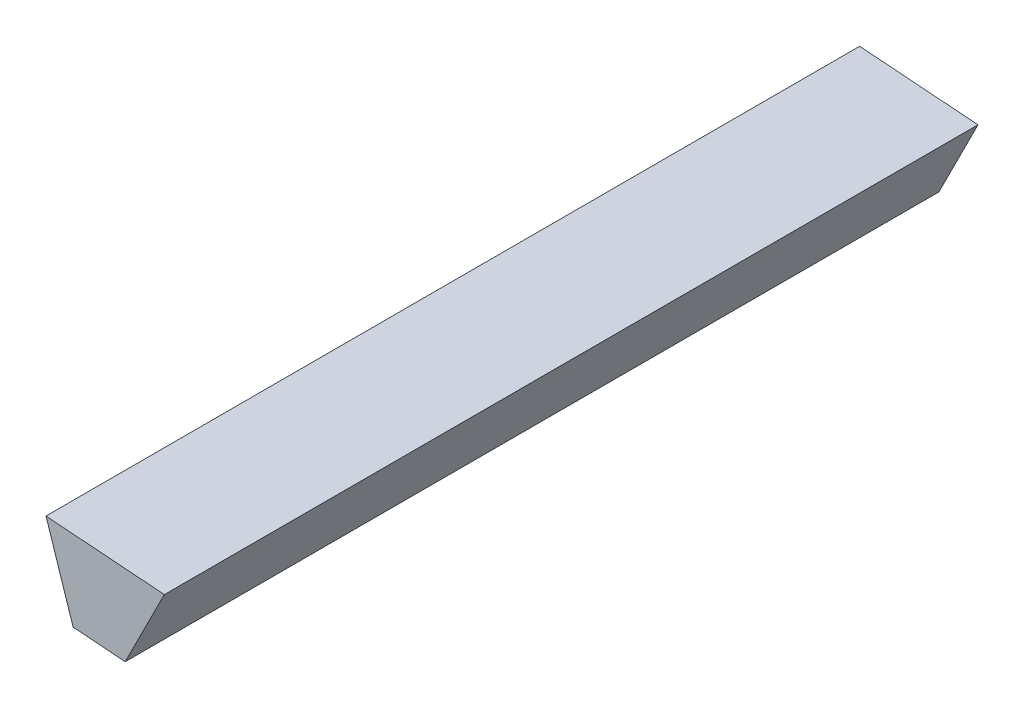
SolidWorks part; units mm, degrees
ref_plane "Спереди" through (0, 0, 0) normal (0, 0, 1) x (1, 0, 0)
ref_plane "Сверху" through (0, 0, 0) normal (0, 1, 0) x (1, 0, 0)
ref_plane "Справа" through (0, 0, 0) normal (1, 0, 0) x (0, 0, -1)
sketch "Эскиз1" plane through (0, 0, 0) normal (0, 0, 1) x (1, 0, 0)
  line L0 (0, 0) -> (0, 56) construction
  line L1 (-2, 55.9643) -> (-3, 52.915)
  line L2 (2, 55.9643) -> (3, 52.915)
  line L3 (6.3634, 55.6373) -> (4.9201, 52.7711)
  line L4 (10.3187, 55.0411) -> (10.8531, 51.8769)
  line L5 (14.5846, 54.0674) -> (12.7303, 51.4484)
  line L6 (18.4069, 52.8884) -> (18.4637, 49.6799)
  line L7 (22.4801, 51.2898) -> (20.2561, 48.9764)
  line L8 (26.0839, 49.5543) -> (25.6619, 46.3731)
  line L9 (29.8733, 47.3665) -> (27.3294, 45.4104)
  line L10 (33.1783, 45.1132) -> (32.2868, 42.0305)
  line L11 (36.5993, 42.3851) -> (33.7922, 40.83)
  line L12 (39.5315, 39.6644) -> (38.1905, 36.7489)
  line L13 (42.5077, 36.4568) -> (39.5002, 35.3375)
  line L14 (45.0016, 33.3295) -> (43.2411, 30.6465)
  line L15 (47.4665, 29.7142) -> (44.3258, 29.0556)
  line L16 (49.4665, 26.2501) -> (47.3258, 23.8594)
  line L17 (51.365, 22.3078) -> (48.1612, 22.1247)
  line L18 (52.8264, 18.5843) -> (50.3532, 16.5394)
  line L19 (54.1161, 14.4031) -> (50.9208, 14.6995)
  line L20 (55.0062, 10.5034) -> (52.2559, 8.8499)
  line L21 (55.6583, 6.1766) -> (52.5429, 6.946)
  line L22 (55.9572, 2.1878) -> (52.9913, 0.9627)
  line L23 (55.9572, -2.1878) -> (52.9913, -0.9627)
  line L24 (55.6583, -6.1766) -> (52.5429, -6.946)
  line L25 (55.0062, -10.5034) -> (52.2559, -8.8499)
  line L26 (54.1161, -14.4031) -> (50.9208, -14.6995)
  line L27 (52.8264, -18.5843) -> (50.3532, -16.5394)
  line L28 (51.365, -22.3078) -> (48.1612, -22.1247)
  line L29 (49.4665, -26.2501) -> (47.3258, -23.8594)
  line L30 (47.4665, -29.7142) -> (44.3258, -29.0556)
  line L31 (45.0016, -33.3295) -> (43.2411, -30.6465)
  line L32 (42.5077, -36.4568) -> (39.5002, -35.3375)
  line L33 (39.5315, -39.6644) -> (38.1905, -36.7489)
  line L34 (36.5993, -42.3851) -> (33.7922, -40.83)
  line L35 (33.1783, -45.1132) -> (32.2868, -42.0305)
  line L36 (29.8733, -47.3665) -> (27.3294, -45.4104)
  line L37 (26.0839, -49.5543) -> (25.6619, -46.3731)
  line L38 (22.4801, -51.2898) -> (20.2561, -48.9764)
  line L39 (18.4069, -52.8884) -> (18.4637, -49.6799)
  line L40 (14.5846, -54.0674) -> (12.7303, -51.4484)
  line L41 (10.3187, -55.0411) -> (10.8531, -51.8769)
  line L42 (6.3634, -55.6373) -> (4.9201, -52.7711)
  line L43 (2, -55.9643) -> (3, -52.915)
  line L44 (-2, -55.9643) -> (-3, -52.915)
  line L45 (-6.3634, -55.6373) -> (-4.9201, -52.7711)
  line L46 (-10.3187, -55.0411) -> (-10.8531, -51.8769)
  line L47 (-14.5846, -54.0674) -> (-12.7303, -51.4484)
  line L48 (-18.4069, -52.8884) -> (-18.4637, -49.6799)
  line L49 (-22.4801, -51.2898) -> (-20.2561, -48.9764)
  line L50 (-26.0839, -49.5543) -> (-25.6619, -46.3731)
  line L51 (-29.8733, -47.3665) -> (-27.3294, -45.4104)
  line L52 (-33.1783, -45.1132) -> (-32.2868, -42.0305)
  line L53 (-36.5993, -42.3851) -> (-33.7922, -40.83)
  line L54 (-39.5315, -39.6644) -> (-38.1905, -36.7489)
  line L55 (-42.5077, -36.4568) -> (-39.5002, -35.3375)
  line L56 (-45.0016, -33.3295) -> (-43.2411, -30.6465)
  line L57 (-47.4665, -29.7142) -> (-44.3258, -29.0556)
  line L58 (-49.4665, -26.2501) -> (-47.3258, -23.8594)
  line L59 (-51.365, -22.3078) -> (-48.1612, -22.1247)
  line L60 (-52.8264, -18.5843) -> (-50.3532, -16.5394)
  line L61 (-54.1161, -14.4031) -> (-50.9208, -14.6995)
  line L62 (-55.0062, -10.5034) -> (-52.2559, -8.8499)
  line L63 (-55.6583, -6.1766) -> (-52.5429, -6.946)
  line L64 (-55.9572, -2.1878) -> (-52.9913, -0.9627)
  line L65 (-55.9572, 2.1878) -> (-52.9913, 0.9627)
  line L66 (-55.6583, 6.1766) -> (-52.5429, 6.946)
  line L67 (-55.0062, 10.5034) -> (-52.2559, 8.8499)
  line L68 (-54.1161, 14.4031) -> (-50.9208, 14.6995)
  line L69 (-52.8264, 18.5843) -> (-50.3532, 16.5394)
  line L70 (-51.365, 22.3078) -> (-48.1612, 22.1247)
  line L71 (-49.4665, 26.2501) -> (-47.3258, 23.8594)
  line L72 (-47.4665, 29.7142) -> (-44.3258, 29.0556)
  line L73 (-45.0016, 33.3295) -> (-43.2411, 30.6465)
  line L74 (-42.5077, 36.4568) -> (-39.5002, 35.3375)
  line L75 (-39.5315, 39.6644) -> (-38.1905, 36.7489)
  line L76 (-36.5993, 42.3851) -> (-33.7922, 40.83)
  line L77 (-33.1783, 45.1132) -> (-32.2868, 42.0305)
  line L78 (-29.8733, 47.3665) -> (-27.3294, 45.4104)
  line L79 (-26.0839, 49.5543) -> (-25.6619, 46.3731)
  line L80 (-22.4801, 51.2898) -> (-20.2561, 48.9764)
  line L81 (-18.4069, 52.8884) -> (-18.4637, 49.6799)
  line L82 (-14.5846, 54.0674) -> (-12.7303, 51.4484)
  line L83 (-10.3187, 55.0411) -> (-10.8531, 51.8769)
  line L84 (-6.3634, 55.6373) -> (-4.9201, 52.7711)
  arc A0 (2, 55.9643) -> (-2, 55.9643) centre (0, 0) ccw
  arc A1 (-3, 52.915) -> (-3.965, 52.8515) centre (0, 0) ccw
  arc A2 (3, 52.915) -> (3.965, 52.8515) centre (0, 0) cw
  arc A3 (4.9201, 52.7711) -> (3.9564, 52.8521) centre (0, 0) ccw
  arc A4 (10.3187, 55.0411) -> (6.3634, 55.6373) centre (0, 0) ccw
  arc A5 (10.8531, 51.8769) -> (11.7978, 51.6702) centre (0, 0) cw
  arc A6 (12.7303, 51.4484) -> (11.7894, 51.6721) centre (0, 0) ccw
  arc A7 (18.4069, 52.8884) -> (14.5846, 54.0674) centre (0, 0) ccw
  arc A8 (18.4637, 49.6799) -> (19.3671, 49.3347) centre (0, 0) cw
  arc A9 (20.2561, 48.9764) -> (19.3591, 49.3379) centre (0, 0) ccw
  arc A10 (26.0839, 49.5543) -> (22.4801, 51.2898) centre (0, 0) ccw
  arc A11 (25.6619, 46.3731) -> (26.5037, 45.8972) centre (0, 0) cw
  arc A12 (27.3294, 45.4104) -> (26.4963, 45.9015) centre (0, 0) ccw
  arc A13 (33.1783, 45.1132) -> (29.8733, 47.3665) centre (0, 0) ccw
  arc A14 (32.2868, 42.0305) -> (33.0483, 41.4344) centre (0, 0) cw
  arc A15 (33.7922, 40.83) -> (33.0416, 41.4398) centre (0, 0) ccw
  arc A16 (39.5315, 39.6644) -> (36.5993, 42.3851) centre (0, 0) ccw
  arc A17 (38.1905, 36.7489) -> (38.8547, 36.046) centre (0, 0) cw
  arc A18 (39.5002, 35.3375) -> (38.8488, 36.0523) centre (0, 0) ccw
  arc A19 (45.0016, 33.3295) -> (42.5077, 36.4568) centre (0, 0) ccw
  arc A20 (43.2411, 30.6465) -> (43.7931, 29.8524) centre (0, 0) cw
  arc A21 (44.3258, 29.0556) -> (43.7882, 29.8595) centre (0, 0) ccw
  arc A22 (49.4665, 26.2501) -> (47.4665, 29.7142) centre (0, 0) ccw
  arc A23 (47.3258, 23.8594) -> (47.7532, 22.9919) centre (0, 0) cw
  arc A24 (48.1612, 22.1247) -> (47.7495, 22.9997) centre (0, 0) ccw
  arc A25 (52.8264, 18.5843) -> (51.365, 22.3078) centre (0, 0) ccw
  arc A26 (50.3532, 16.5394) -> (50.6466, 15.6179) centre (0, 0) cw
  arc A27 (50.9208, 14.6995) -> (50.6441, 15.6261) centre (0, 0) ccw
  arc A28 (55.0062, 10.5034) -> (54.1161, 14.4031) centre (0, 0) ccw
  arc A29 (52.2559, 8.8499) -> (52.4087, 7.895) centre (0, 0) cw
  arc A30 (52.5429, 6.946) -> (52.4074, 7.9035) centre (0, 0) ccw
  arc A31 (55.9572, 2.1878) -> (55.6583, 6.1766) centre (0, 0) ccw
  arc A32 (52.9913, 0.9627) -> (53, -0.0043) centre (0, 0) cw
  arc A33 (52.9913, -0.9627) -> (53, 0.0043) centre (0, 0) ccw
  arc A34 (55.6583, -6.1766) -> (55.9572, -2.1878) centre (0, 0) ccw
  arc A35 (52.5429, -6.946) -> (52.4074, -7.9035) centre (0, 0) cw
  arc A36 (52.2559, -8.8499) -> (52.4087, -7.895) centre (0, 0) ccw
  arc A37 (54.1161, -14.4031) -> (55.0062, -10.5034) centre (0, 0) ccw
  arc A38 (50.9208, -14.6995) -> (50.6441, -15.6261) centre (0, 0) cw
  arc A39 (50.3532, -16.5394) -> (50.6466, -15.6179) centre (0, 0) ccw
  arc A40 (51.365, -22.3078) -> (52.8264, -18.5843) centre (0, 0) ccw
  arc A41 (48.1612, -22.1247) -> (47.7495, -22.9997) centre (0, 0) cw
  arc A42 (47.3258, -23.8594) -> (47.7532, -22.9919) centre (0, 0) ccw
  arc A43 (47.4665, -29.7142) -> (49.4665, -26.2501) centre (0, 0) ccw
  arc A44 (44.3258, -29.0556) -> (43.7882, -29.8595) centre (0, 0) cw
  arc A45 (43.2411, -30.6465) -> (43.7931, -29.8524) centre (0, 0) ccw
  arc A46 (42.5077, -36.4568) -> (45.0016, -33.3295) centre (0, 0) ccw
  arc A47 (39.5002, -35.3375) -> (38.8488, -36.0523) centre (0, 0) cw
  arc A48 (38.1905, -36.7489) -> (38.8547, -36.046) centre (0, 0) ccw
  arc A49 (36.5993, -42.3851) -> (39.5315, -39.6644) centre (0, 0) ccw
  arc A50 (33.7922, -40.83) -> (33.0416, -41.4398) centre (0, 0) cw
  arc A51 (32.2868, -42.0305) -> (33.0483, -41.4344) centre (0, 0) ccw
  arc A52 (29.8733, -47.3665) -> (33.1783, -45.1132) centre (0, 0) ccw
  arc A53 (27.3294, -45.4104) -> (26.4963, -45.9015) centre (0, 0) cw
  arc A54 (25.6619, -46.3731) -> (26.5037, -45.8972) centre (0, 0) ccw
  arc A55 (22.4801, -51.2898) -> (26.0839, -49.5543) centre (0, 0) ccw
  arc A56 (20.2561, -48.9764) -> (19.3591, -49.3379) centre (0, 0) cw
  arc A57 (18.4637, -49.6799) -> (19.3671, -49.3347) centre (0, 0) ccw
  arc A58 (14.5846, -54.0674) -> (18.4069, -52.8884) centre (0, 0) ccw
  arc A59 (12.7303, -51.4484) -> (11.7894, -51.6721) centre (0, 0) cw
  arc A60 (10.8531, -51.8769) -> (11.7978, -51.6702) centre (0, 0) ccw
  arc A61 (6.3634, -55.6373) -> (10.3187, -55.0411) centre (0, 0) ccw
  arc A62 (4.9201, -52.7711) -> (3.9564, -52.8521) centre (0, 0) cw
  arc A63 (3, -52.915) -> (3.965, -52.8515) centre (0, 0) ccw
  arc A64 (-2, -55.9643) -> (2, -55.9643) centre (0, 0) ccw
  arc A65 (-3, -52.915) -> (-3.965, -52.8515) centre (0, 0) cw
  arc A66 (-4.9201, -52.7711) -> (-3.9564, -52.8521) centre (0, 0) ccw
  arc A67 (-10.3187, -55.0411) -> (-6.3634, -55.6373) centre (0, 0) ccw
  arc A68 (-10.8531, -51.8769) -> (-11.7978, -51.6702) centre (0, 0) cw
  arc A69 (-12.7303, -51.4484) -> (-11.7894, -51.6721) centre (0, 0) ccw
  arc A70 (-18.4069, -52.8884) -> (-14.5846, -54.0674) centre (0, 0) ccw
  arc A71 (-18.4637, -49.6799) -> (-19.3671, -49.3347) centre (0, 0) cw
  arc A72 (-20.2561, -48.9764) -> (-19.3591, -49.3379) centre (0, 0) ccw
  arc A73 (-26.0839, -49.5543) -> (-22.4801, -51.2898) centre (0, 0) ccw
  arc A74 (-25.6619, -46.3731) -> (-26.5037, -45.8972) centre (0, 0) cw
  arc A75 (-27.3294, -45.4104) -> (-26.4963, -45.9015) centre (0, 0) ccw
  arc A76 (-33.1783, -45.1132) -> (-29.8733, -47.3665) centre (0, 0) ccw
  arc A77 (-32.2868, -42.0305) -> (-33.0483, -41.4344) centre (0, 0) cw
  arc A78 (-33.7922, -40.83) -> (-33.0416, -41.4398) centre (0, 0) ccw
  arc A79 (-39.5315, -39.6644) -> (-36.5993, -42.3851) centre (0, 0) ccw
  arc A80 (-38.1905, -36.7489) -> (-38.8547, -36.046) centre (0, 0) cw
  arc A81 (-39.5002, -35.3375) -> (-38.8488, -36.0523) centre (0, 0) ccw
  arc A82 (-45.0016, -33.3295) -> (-42.5077, -36.4568) centre (0, 0) ccw
  arc A83 (-43.2411, -30.6465) -> (-43.7931, -29.8524) centre (0, 0) cw
  arc A84 (-44.3258, -29.0556) -> (-43.7882, -29.8595) centre (0, 0) ccw
  arc A85 (-49.4665, -26.2501) -> (-47.4665, -29.7142) centre (0, 0) ccw
  arc A86 (-47.3258, -23.8594) -> (-47.7532, -22.9919) centre (0, 0) cw
  arc A87 (-48.1612, -22.1247) -> (-47.7495, -22.9997) centre (0, 0) ccw
  arc A88 (-52.8264, -18.5843) -> (-51.365, -22.3078) centre (0, 0) ccw
  arc A89 (-50.3532, -16.5394) -> (-50.6466, -15.6179) centre (0, 0) cw
  arc A90 (-50.9208, -14.6995) -> (-50.6441, -15.6261) centre (0, 0) ccw
  arc A91 (-55.0062, -10.5034) -> (-54.1161, -14.4031) centre (0, 0) ccw
  arc A92 (-52.2559, -8.8499) -> (-52.4087, -7.895) centre (0, 0) cw
  arc A93 (-52.5429, -6.946) -> (-52.4074, -7.9035) centre (0, 0) ccw
  arc A94 (-55.9572, -2.1878) -> (-55.6583, -6.1766) centre (0, 0) ccw
  arc A95 (-52.9913, -0.9627) -> (-53, 0.0043) centre (0, 0) cw
  arc A96 (-52.9913, 0.9627) -> (-53, -0.0043) centre (0, 0) ccw
  arc A97 (-55.6583, 6.1766) -> (-55.9572, 2.1878) centre (0, 0) ccw
  arc A98 (-52.5429, 6.946) -> (-52.4074, 7.9035) centre (0, 0) cw
  arc A99 (-52.2559, 8.8499) -> (-52.4087, 7.895) centre (0, 0) ccw
  arc A100 (-54.1161, 14.4031) -> (-55.0062, 10.5034) centre (0, 0) ccw
  arc A101 (-50.9208, 14.6995) -> (-50.6441, 15.6261) centre (0, 0) cw
  arc A102 (-50.3532, 16.5394) -> (-50.6466, 15.6179) centre (0, 0) ccw
  arc A103 (-51.365, 22.3078) -> (-52.8264, 18.5843) centre (0, 0) ccw
  arc A104 (-48.1612, 22.1247) -> (-47.7495, 22.9997) centre (0, 0) cw
  arc A105 (-47.3258, 23.8594) -> (-47.7532, 22.9919) centre (0, 0) ccw
  arc A106 (-47.4665, 29.7142) -> (-49.4665, 26.2501) centre (0, 0) ccw
  arc A107 (-44.3258, 29.0556) -> (-43.7882, 29.8595) centre (0, 0) cw
  arc A108 (-43.2411, 30.6465) -> (-43.7931, 29.8524) centre (0, 0) ccw
  arc A109 (-42.5077, 36.4568) -> (-45.0016, 33.3295) centre (0, 0) ccw
  arc A110 (-39.5002, 35.3375) -> (-38.8488, 36.0523) centre (0, 0) cw
  arc A111 (-38.1905, 36.7489) -> (-38.8547, 36.046) centre (0, 0) ccw
  arc A112 (-36.5993, 42.3851) -> (-39.5315, 39.6644) centre (0, 0) ccw
  arc A113 (-33.7922, 40.83) -> (-33.0416, 41.4398) centre (0, 0) cw
  arc A114 (-32.2868, 42.0305) -> (-33.0483, 41.4344) centre (0, 0) ccw
  arc A115 (-29.8733, 47.3665) -> (-33.1783, 45.1132) centre (0, 0) ccw
  arc A116 (-27.3294, 45.4104) -> (-26.4963, 45.9015) centre (0, 0) cw
  arc A117 (-25.6619, 46.3731) -> (-26.5037, 45.8972) centre (0, 0) ccw
  arc A118 (-22.4801, 51.2898) -> (-26.0839, 49.5543) centre (0, 0) ccw
  arc A119 (-20.2561, 48.9764) -> (-19.3591, 49.3379) centre (0, 0) cw
  arc A120 (-18.4637, 49.6799) -> (-19.3671, 49.3347) centre (0, 0) ccw
  arc A121 (-14.5846, 54.0674) -> (-18.4069, 52.8884) centre (0, 0) ccw
  arc A122 (-12.7303, 51.4484) -> (-11.7894, 51.6721) centre (0, 0) cw
  arc A123 (-10.8531, 51.8769) -> (-11.7978, 51.6702) centre (0, 0) ccw
  arc A124 (-6.3634, 55.6373) -> (-10.3187, 55.0411) centre (0, 0) ccw
  arc A125 (-4.9201, 52.7711) -> (-3.9564, 52.8521) centre (0, 0) cw
  circle A126 centre (0, 0) radius 50
  point P258 (0, 0)
  dimension "D1" = 56
  dimension "D3" = 53
  dimension "D7" = 100
  dimension "D2" = 2
  dimension "D4" = 3
  dimension "D5" = 3.965
  dimension "D6" = 42
extrude "Бобышка-Вытянуть1" add sketch "Эскиз1" along normal mid plane 30
sketch "Эскиз2" plane through (0, 0, -15) normal (0, 0, -1) x (-1, 0, 0)
  line L0 (0, 0) -> (0, 41.684) construction
  line L1 (3.4537, 43) -> (-3.4537, 43)
  line L2 (-8.2776, 36.6844) -> (-4.8039, 23.9475)
  line L3 (-0.9448, 21) -> (0.9448, 21)
  line L4 (8.2776, 36.6844) -> (4.8039, 23.9475)
  line L5 (41.9627, 10.003) -> (39.8282, 16.5724)
  line L6 (32.331, 19.2085) -> (21.291, 11.9689)
  line L7 (37.4469, 3.4637) -> (24.2599, 2.8314)
  line L8 (19.6802, 7.3879) -> (20.2642, 5.5908)
  line L9 (22.4806, -36.8178) -> (28.0689, -32.7577)
  line L10 (28.2592, -24.8129) -> (17.9624, -16.5503)
  line L11 (14.8659, -34.5437) -> (10.1896, -22.1976)
  line L12 (13.1079, -16.434) -> (11.5791, -17.5447)
  line L13 (-28.0689, -32.7577) -> (-22.4806, -36.8178)
  line L14 (-14.8659, -34.5437) -> (-10.1896, -22.1976)
  line L15 (-28.2592, -24.8129) -> (-17.9624, -16.5503)
  line L16 (-11.5791, -17.5447) -> (-13.1079, -16.434)
  line L17 (-39.8282, 16.5724) -> (-41.9627, 10.003)
  line L18 (-37.4469, 3.4637) -> (-24.2599, 2.8314)
  line L19 (-32.331, 19.2085) -> (-21.291, 11.9689)
  line L20 (-20.2642, 5.5908) -> (-19.6802, 7.3879)
  circle A0 centre (0, 0) radius 15
  arc A1 (-3.4537, 43) -> (-8.2776, 36.6844) centre (-3.4537, 38) ccw
  arc A2 (-4.8039, 23.9475) -> (-0.9448, 21) centre (-0.9448, 25) ccw
  arc A3 (4.8039, 23.9475) -> (0.9448, 21) centre (0.9448, 25) cw
  arc A4 (3.4537, 43) -> (8.2776, 36.6844) centre (3.4537, 38) cw
  arc A5 (39.8282, 16.5724) -> (32.331, 19.2085) centre (35.0729, 15.0274) ccw
  arc A6 (21.291, 11.9689) -> (19.6802, 7.3879) centre (23.4844, 8.624) ccw
  arc A7 (24.2599, 2.8314) -> (20.2642, 5.5908) centre (24.0684, 6.8269) cw
  arc A8 (41.9627, 10.003) -> (37.4469, 3.4637) centre (37.2074, 8.4579) cw
  arc A9 (28.0689, -32.7577) -> (28.2592, -24.8129) centre (25.13, -28.7126) ccw
  arc A10 (17.9624, -16.5503) -> (13.1079, -16.434) centre (15.459, -19.6701) ccw
  arc A11 (10.1896, -22.1976) -> (11.5791, -17.5447) centre (13.9303, -20.7808) cw
  arc A12 (22.4806, -36.8178) -> (14.8659, -34.5437) centre (19.5417, -32.7727) cw
  arc A13 (-22.4806, -36.8178) -> (-14.8659, -34.5437) centre (-19.5417, -32.7727) ccw
  arc A14 (-10.1896, -22.1976) -> (-11.5791, -17.5447) centre (-13.9303, -20.7808) ccw
  arc A15 (-17.9624, -16.5503) -> (-13.1079, -16.434) centre (-15.459, -19.6701) cw
  arc A16 (-28.0689, -32.7577) -> (-28.2592, -24.8129) centre (-25.13, -28.7126) cw
  arc A17 (-41.9627, 10.003) -> (-37.4469, 3.4637) centre (-37.2074, 8.4579) ccw
  arc A18 (-24.2599, 2.8314) -> (-20.2642, 5.5908) centre (-24.0684, 6.8269) ccw
  arc A19 (-21.291, 11.9689) -> (-19.6802, 7.3879) centre (-23.4844, 8.624) cw
  arc A20 (-39.8282, 16.5724) -> (-32.331, 19.2085) centre (-35.0729, 15.0274) cw
  circle A21 centre (0, 0) radius 50
  point P10 (-10, 43)
  point P14 (-4, 21)
  point P16 (0, 21)
  point P21 (0, 43)
  point P34 (40.8954, 13.2877)
  point P47 (25.2748, -34.7877)
  point P60 (-25.2748, -34.7877)
  point P73 (-40.8954, 13.2877)
  point P74 (0, 0)
  dimension "D1" = 30
  dimension "D6" = 5
  dimension "D7" = 4
  dimension "D9" = 100
  dimension "D2" = 21
  dimension "D3" = 22
  dimension "D4" = 10
  dimension "D5" = 4
  dimension "D8" = 5
extrude "Бобышка-Вытянуть2" add sketch "Эскиз2" against normal blind 25
sketch "Эскиз3" plane through (0, 0, 0) normal (0, 0, 1) x (1, 0, 0)
  line L0 (2, 55.9643) -> (6.3634, 55.6373)
  line L1 (6.3634, 55.6373) -> (4.9201, 52.7711)
  line L2 (4.9201, 52.7711) -> (3, 52.915)
  line L3 (3, 52.915) -> (2, 55.9643)
extrude "Бобышка-Вытянуть3" add sketch "Эскиз3" along normal mid plane 30 separate body
delete or keep bodies "Тело-Удалить/Сохранить 1" type delete bodies bodies 102
